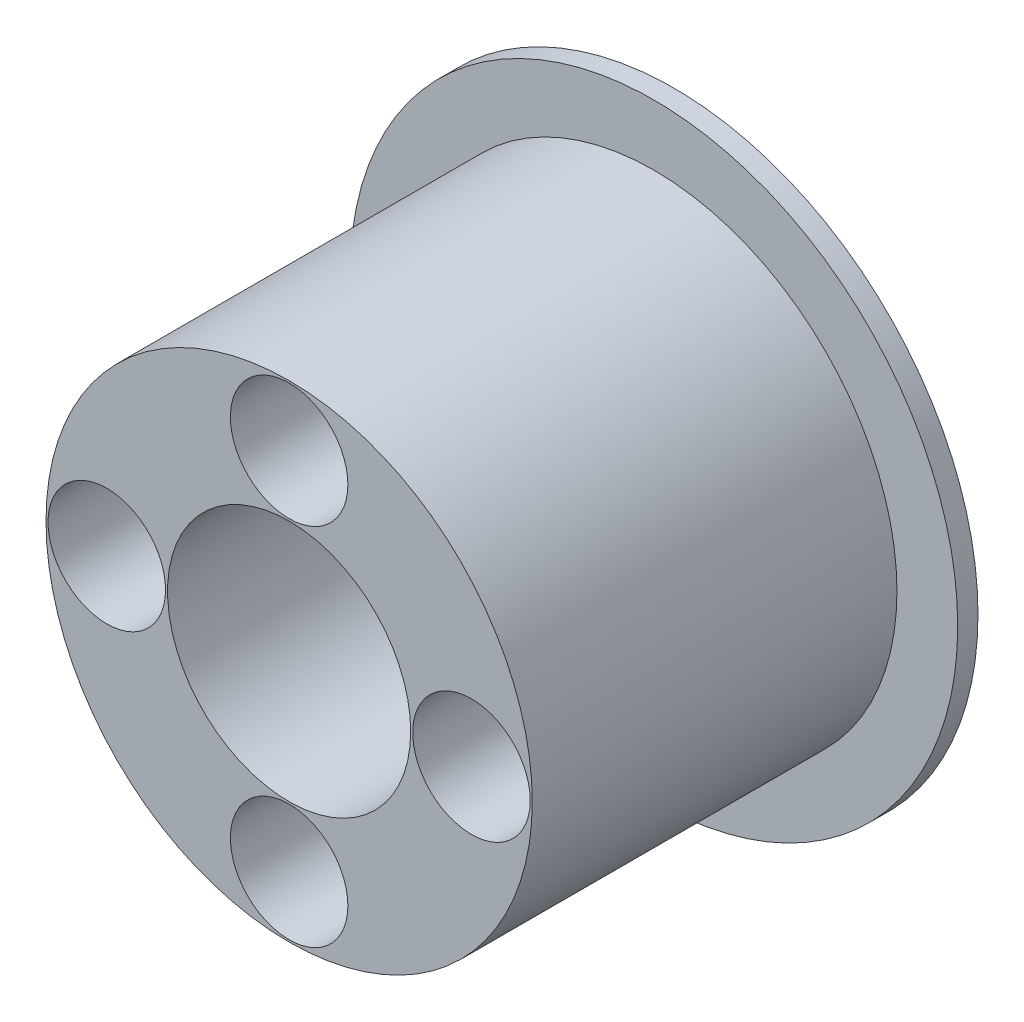
SolidWorks part; units mm, degrees
ref_plane "Ebene vorne" through (0, 0, 0) normal (0, 0, 1) x (1, 0, 0)
ref_plane "Ebene oben" through (0, 0, 0) normal (0, 1, 0) x (1, 0, 0)
ref_plane "Ebene rechts" through (0, 0, 0) normal (1, 0, 0) x (0, 0, -1)
sketch "Skizze1" plane through (0, 0, 0) normal (0, 0, 1) x (1, 0, 0)
  circle A0 centre (0, 0) radius 12
  circle A1 centre (0, 0) radius 9
  circle A2 centre (9, 0) radius 1.5
  circle A3 centre (0, -9) radius 1.5
  circle A4 centre (-9, 0) radius 1.5
  circle A5 centre (0, 9) radius 1.5
  point P15 (0, 0)
  dimension "D1" = 24
  dimension "D2" = 18
  dimension "D3" = 4
extrude "Aufsatz-Linear austragen1" add sketch "Skizze1" along normal blind 18 contours A1 | A0 A1 | A4 | A2 | A5 | A3
sketch "Skizze4" plane through (0, 0, 0) normal (0, 0, -1) x (-1, 0, 0)
  circle A0 centre (0, 0) radius 15
  circle A1 centre (0, 9) radius 1.5
  circle A2 centre (9, 0) radius 1.5
  circle A3 centre (0, -9) radius 1.5
  circle A4 centre (-9, 0) radius 1.5
extrude "Aufsatz-Linear austragen2" add sketch "Skizze4" along normal blind 1
sketch "Skizze2" plane through (0, 0, 18) normal (0, 0, 1) x (1, 0, 0)
  circle A0 centre (0, 9) radius 2.9
  circle A1 centre (9, 0) radius 2.9
  circle A2 centre (0, -9) radius 2.9
  circle A3 centre (-9, 0) radius 2.9
  point P12 (0, 0)
  dimension "D1" = 4
extrude "Schnitt-Linear austragen4" cut sketch "Skizze2" against normal offset from surface (14 mm away) 5 up to face at (-1.5, -9, -1)
sketch "Skizze6" plane through (0, 0, 18) normal (0, 0, 1) x (1, 0, 0)
  line L0 (-1.5, 2) -> (1.5, 2)
  circle A0 centre (0, 0) radius 2.5
  dimension "D1" = 5
  dimension "D2" = 3
extrude "Schnitt-Linear austragen5" cut sketch "Skizze6" against normal blind 23 contours L0 A0
sketch "Skizze9" plane through (0, 0, 18) normal (0, 0, 1) x (1, 0, 0)
  circle A0 centre (0, 0) radius 2.5
extrude "Schnitt-Linear austragen7" cut sketch "Skizze9" against normal blind 5
sketch "Skizze11" plane through (0, 0, 18) normal (0, 0, 1) x (1, 0, 0)
  circle A0 centre (0, 0) radius 6
  point P2 (0, 0)
extrude "Schnitt-Linear austragen9" cut sketch "Skizze11" against normal blind 20
